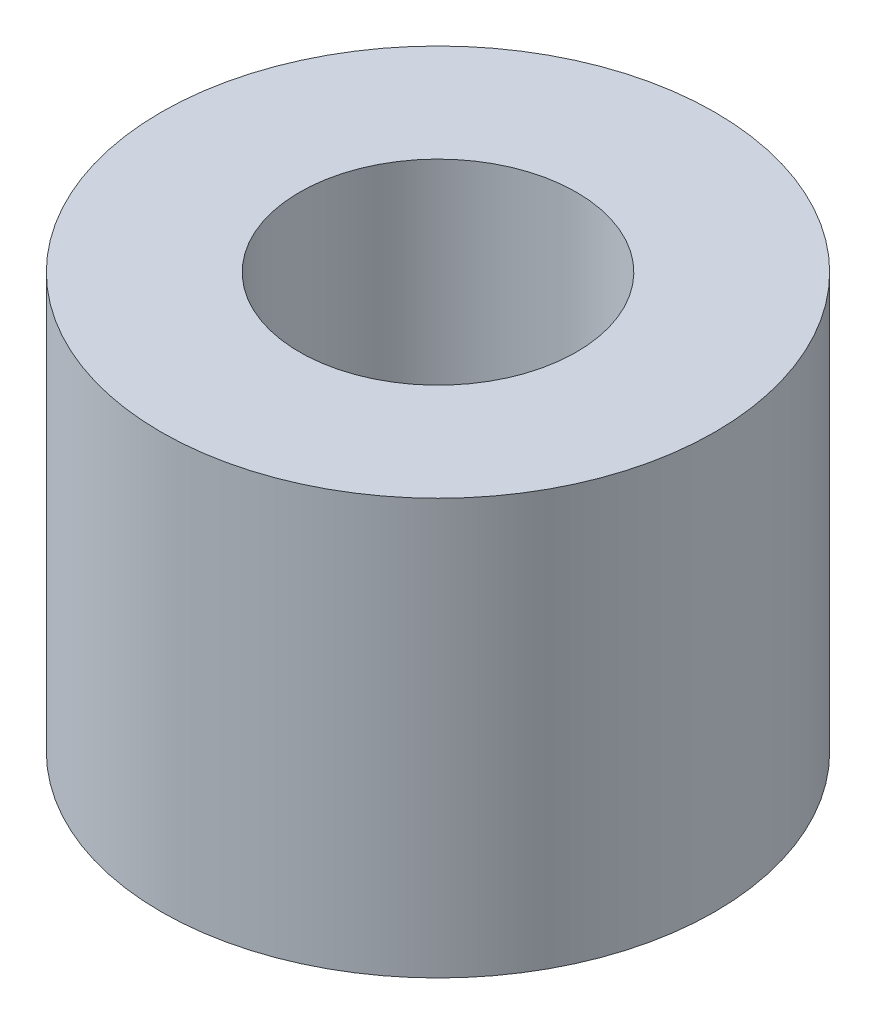
SolidWorks part; units mm, degrees
other "Aileron Spacer"
ref_plane "Front Plane" through (0, 0, 0) normal (0, 0, 1) x (1, 0, 0)
ref_plane "Top Plane" through (0, 0, 0) normal (0, 1, 0) x (1, 0, 0)
ref_plane "Right Plane" through (0, 0, 0) normal (1, 0, 0) x (0, 0, -1)
sketch "Sketch2" plane through (0, 0, 0) normal (0, 1, 0) x (1, 0, 0)
  circle A0 centre (0, 0) radius 3.175
  circle A1 centre (0, 0) radius 6.35
  dimension "D1" = 3.175
extrude "Boss-Extrude1" add sketch "Sketch2" along normal blind 9.525
